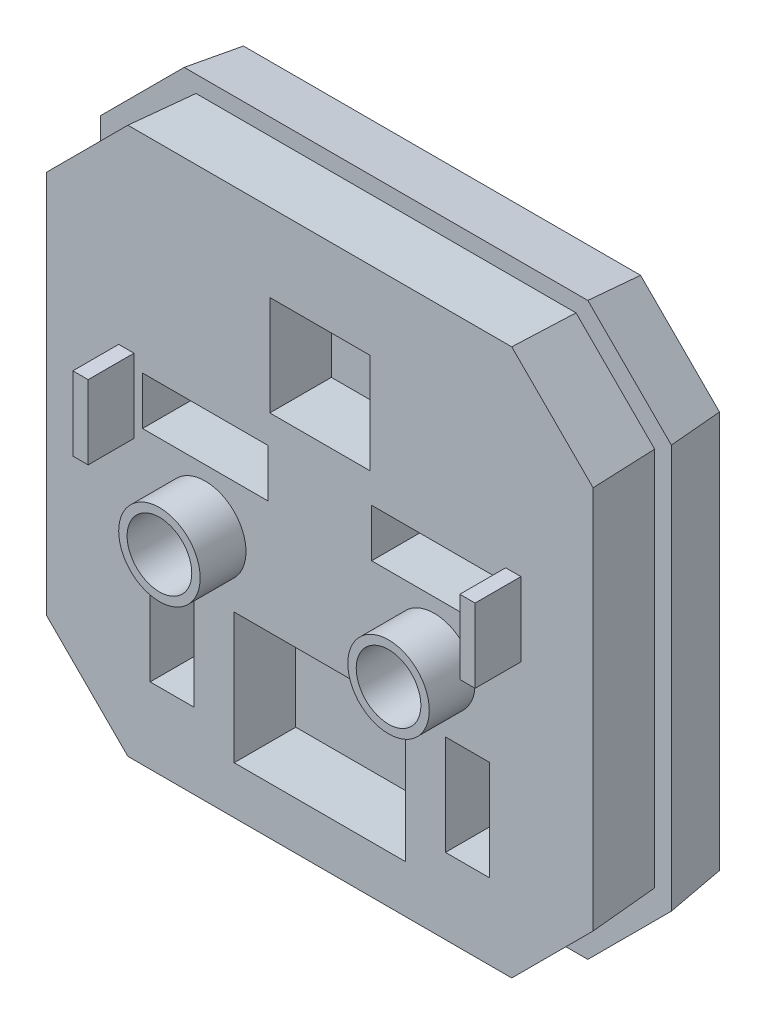
SolidWorks part; units mm, degrees
ref_plane "Front Plane" through (0, 0, 0) normal (0, 0, 1) x (1, 0, 0)
ref_plane "Top Plane" through (0, 0, 0) normal (0, 1, 0) x (1, 0, 0)
ref_plane "Right Plane" through (0, 0, 0) normal (1, 0, 0) x (0, 0, -1)
sketch "Sketch1" plane through (0, 0, 0) normal (0, 0, 1) x (1, 0, 0)
  line L0 (-78, 109) -> (78, 109)
  line L1 (78, 109) -> (109, 78)
  line L2 (109, 78) -> (109, -78)
  line L3 (109, -78) -> (78, -109)
  line L4 (78, -109) -> (-78, -109)
  line L5 (-78, -109) -> (-109, -78)
  line L6 (-109, -78) -> (-109, 78)
  line L7 (-109, 78) -> (-78, 109)
  line L9 (-49, 86) -> (49, 86)
  line L10 (-49, 86) -> (-49, 102)
  line L11 (-49, 102) -> (49, 102)
  line L12 (49, 86) -> (49, 102)
  circle A0 centre (-45, -14.5) radius 12.7
  circle A1 centre (45, -14.5) radius 12.7
extrude "Boss-Extrude1" add sketch "Sketch1" along normal blind 22 draft 8 draft outward yes
sketch "Sketch2" plane through (0, 0, 0) normal (0, 0, 1) x (1, 0, 0)
  line L0 (-74, 104) -> (74, 104)
  line L1 (74, 104) -> (104, 74)
  line L2 (104, 74) -> (104, -74)
  line L3 (104, -74) -> (74, -104)
  line L4 (74, -104) -> (-74, -104)
  line L5 (-74, -104) -> (-104, -74)
  line L6 (-104, -74) -> (-104, 74)
  line L7 (-104, 74) -> (-74, 104)
  line L9 (-73, 3.7) -> (-17, 3.7)
  line L10 (-73, 3.7) -> (-73, 29.3)
  line L11 (-73, 29.3) -> (-17, 29.3)
  line L12 (-17, 3.7) -> (-17, 29.3)
  line L14 (17, 3.7) -> (73, 3.7)
  line L15 (17, 3.7) -> (17, 29.3)
  line L16 (17, 29.3) -> (73, 29.3)
  line L17 (73, 3.7) -> (73, 29.3)
  line L19 (-23, 34) -> (23, 34)
  line L20 (-23, 34) -> (-23, 80)
  line L21 (-23, 80) -> (23, 80)
  line L22 (23, 34) -> (23, 80)
  line L24 (-37, -92) -> (37, -92)
  line L25 (-37, -92) -> (-37, -34)
  line L26 (-37, -34) -> (37, -34)
  line L27 (37, -92) -> (37, -34)
  line L29 (-70, -81) -> (-46, -81)
  line L30 (-70, -81) -> (-70, -35)
  line L31 (-70, -35) -> (-46, -35)
  line L32 (-46, -81) -> (-46, -35)
  line L34 (46, -81) -> (70, -81)
  line L35 (46, -81) -> (46, -35)
  line L36 (46, -35) -> (70, -35)
  line L37 (70, -81) -> (70, -35)
  circle A0 centre (-45, -14.5) radius 12.7
  circle A1 centre (45, -14.5) radius 12.7
extrude "Boss-Extrude2" add sketch "Sketch2" along normal blind 48 draft 4 draft outward yes
sketch "Sketch3" plane through (0, 0, 0) normal (0, 0, 1) x (1, 0, 0)
  line L1 (-79, 2) -> (-73, 2)
  line L2 (-79, 2) -> (-79, 31)
  line L3 (-79, 31) -> (-73, 31)
  line L4 (-73, 2) -> (-73, 31)
  line L6 (73, 2) -> (79, 2)
  line L7 (73, 2) -> (73, 31)
  line L8 (73, 31) -> (79, 31)
  line L9 (79, 2) -> (79, 31)
  circle A0 centre (-45, -14.5) radius 16
  circle A1 centre (-45, -14.5) radius 12.7
  circle A2 centre (45, -14.5) radius 16
  circle A3 centre (45, -14.5) radius 12.7
extrude "Boss-Extrude3" add sketch "Sketch3" along normal blind 66
